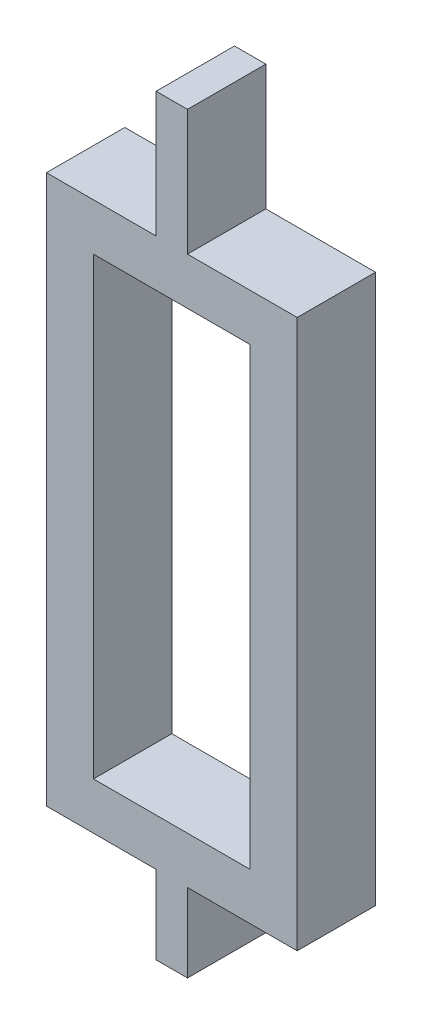
SolidWorks part; units mm, degrees
ref_plane "Front Plane" through (0, 0, 0) normal (0, 0, 1) x (1, 0, 0)
ref_plane "Top Plane" through (0, 0, 0) normal (0, 1, 0) x (1, 0, 0)
ref_plane "Right Plane" through (0, 0, 0) normal (1, 0, 0) x (0, 0, -1)
sketch "Sketch1" plane through (0, 0, 0) normal (0, 0, 1) x (1, 0, 0)
  line L1 (10.16, 0.022) -> (10.16, 44.472)
  line L3 (-10.16, 44.472) -> (-10.16, 0.022)
  line L4 (0, 0) -> (0, -6.328) construction
  line L5 (-10.16, 0.022) -> (-1.27, 0.022)
  line L6 (-1.27, 0.022) -> (-1.27, -6.328)
  line L7 (-1.27, -6.328) -> (1.27, -6.328)
  line L8 (1.27, 0.022) -> (1.27, -6.328)
  line L9 (10.16, 0.022) -> (1.27, 0.022)
  line L10 (10.16, 22.247) -> (-10.16, 22.247) construction
  line L13 (10.16, 44.472) -> (1.27, 44.472)
  line L15 (-10.16, 44.472) -> (-1.27, 44.472)
  line L16 (-1.27, 44.472) -> (-1.27, 54.632)
  line L17 (-1.27, 54.632) -> (1.27, 54.632)
  line L18 (1.27, 54.632) -> (1.27, 44.472)
  dimension "D1" = 2.54
  dimension "D2" = 44.45
  dimension "D3" = 20.32
  dimension "D4" = 6.35
  dimension "D5" = 1.27
  dimension "D6" = 10.16
  dimension "D7" = 22.247
extrude "Boss-Extrude1" add sketch "Sketch1" along normal blind 6.35
sketch "Sketch3" plane through (0, 0, 6.35) normal (0, 0, 1) x (1, 0, 0)
  line L8 (-6.35, 40.662) -> (-6.35, 3.832)
  line L9 (-6.35, 3.832) -> (6.35, 3.832)
  line L10 (6.35, 3.832) -> (6.35, 40.662)
  line L11 (6.35, 40.662) -> (-6.35, 40.662)
  line L12 (-6.35, 40.662) -> (-6.35, 3.832)
  line L14 (6.35, 3.832) -> (6.35, 40.662)
  line L16 (-6.35, 3.832) -> (6.35, 3.832)
  line L21 (6.35, 40.662) -> (-6.35, 40.662)
  dimension "D1" = 3.81
extrude "Cut-Extrude1" cut sketch "Sketch3" against normal blind 6.35 contours L12 L16 L14 L21
